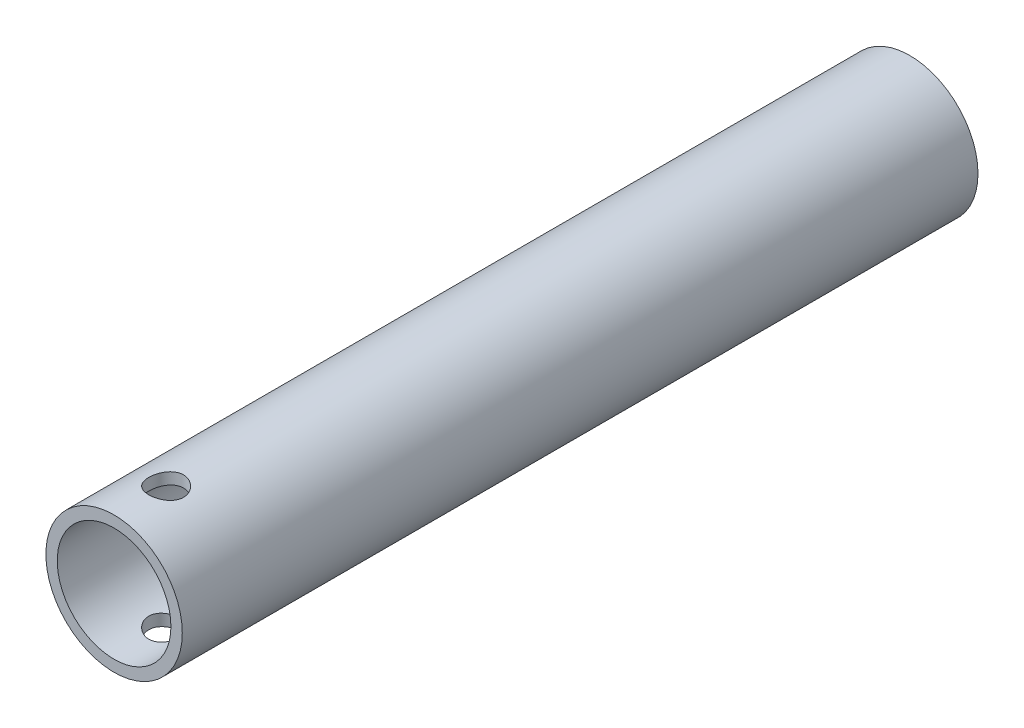
SolidWorks part; units mm, degrees
ref_plane "Front Plane" through (0, 0, 0) normal (0, 0, 1) x (1, 0, 0)
ref_plane "Top Plane" through (0, 0, 0) normal (0, 1, 0) x (1, 0, 0)
ref_plane "Right Plane" through (0, 0, 0) normal (1, 0, 0) x (0, 0, -1)
sketch "Sketch1" plane through (0, 0, 0) normal (0, 0, 1) x (1, 0, 0)
  line L0 (-6, 0) -> (-5, 0) construction
  circle A0 centre (0, 0) radius 5 construction
  circle A1 centre (0, 0) radius 6 construction
  dimension "OD" = 12
  dimension "ID" = 10
  dimension "Wall Thickness" = 1
sketch "Sketch2" plane through (0, 0, 0) normal (1, 0, 0) x (0, 0, -1)
  line L0 (-152.4, -6) -> (152.4, -6) construction
  point P2 (0, -6)
  point P3 (134.4, -6)
  point P4 (-134.4, -6)
  dimension "Length" = 304.8
  dimension "D1" = 18
  dimension "D2" = 18
sketch "Sketch3" plane through (0, 0, 0) normal (0, 0, 1) x (1, 0, 0)
  circle A0 centre (0, 0) radius 5 construction
  circle A1 centre (0, 0) radius 6 construction
  circle A2 centre (0, 0) radius 5
  circle A3 centre (0, 0) radius 6
extrude "Boss-Extrude2" add sketch "Sketch3" along normal up to vertex (152.4 mm away) and the other way up to vertex (152.4 mm away) up to point (0, -6, 152.4) other way up to point (0, -6, -152.4)
sketch "Sketch4" plane through (0, 0, 0) normal (0, 1, 0) x (1, 0, 0)
  line L0 (0, -152.4) -> (0, -98.8028) construction
  line L1 (-6, -152.4) -> (6, -152.4) construction
  circle A0 centre (0, -147.82) radius 1.524
  dimension "D1" = 4.58
  dimension "D2" = 3.048
extrude "Cut-Extrude1" cut sketch "Sketch4" against normal through all both and the other way through all
sketch "Sketch5" plane through (0, 0, -152.4) normal (0, 0, -1) x (-1, 0, 0)
  circle A0 centre (0, 0) radius 6
extrude "Cut-Extrude2" cut sketch "Sketch5" against normal offset from surface (234.8 mm away) 70 up to face at (6, 0, 152.4)
equation "\"D1@Sketch2\"=\"OD@Sketch1\"*1.5"
equation "\"D2@Sketch2\"=\"D1@Sketch2\""
